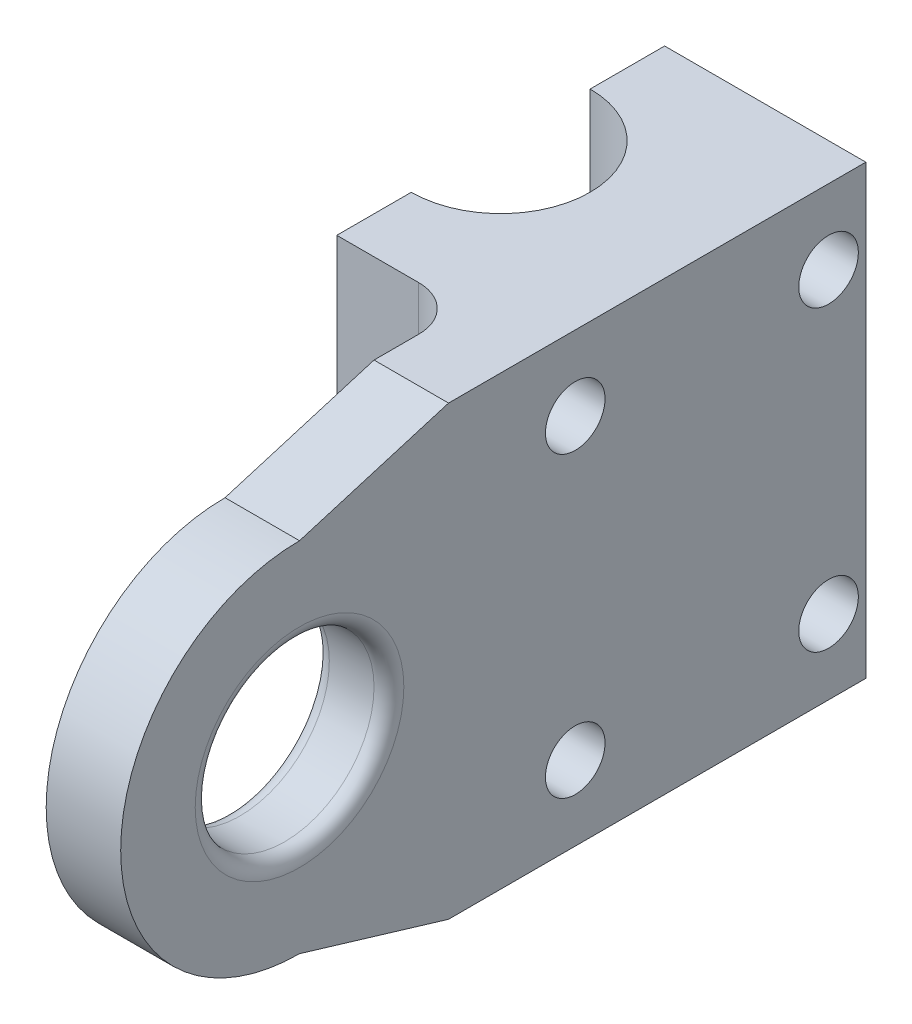
SolidWorks part; units mm, degrees
material "5052-H32"
ref_plane "Front Plane" through (0, 0, 0) normal (0, 0, 1) x (1, 0, 0)
ref_plane "Top Plane" through (0, 0, 0) normal (0, 1, 0) x (1, 0, 0)
ref_plane "Right Plane" through (0, 0, 0) normal (1, 0, 0) x (0, 0, -1)
sketch "Sketch2" plane through (0, 0, 0) normal (0, 1, 0) x (1, 0, 0)
  line L0 (0, 0) -> (0, 50) construction
  line L1 (0, 0) -> (84.2269, 0) construction
  line L2 (0, 50) -> (13.5, 50)
  line L3 (13.5, 50) -> (13.5, 0)
  line L4 (13.5, 0) -> (8.5, 0)
  line L5 (8.5, 0) -> (8.5, 25)
  line L7 (5.5, 28) -> (0, 28)
  line L8 (0, 28) -> (0, 33)
  line L9 (0, 45) -> (0, 50)
  arc A0 (0, 33) -> (0, 45) centre (0, 39) ccw
  arc A1 (8.5, 25) -> (5.5, 28) centre (5.5, 25) ccw
  dimension "D3" = 6
  dimension "D6" = 3
  dimension "D1" = 50
  dimension "D2" = 5
  dimension "D4" = 27
  dimension "D5" = 22
extrude "Boss-Extrude1" add sketch "Sketch2" along normal blind 30
sketch "Sketch3" plane through (13.5, 0, 0) normal (1, 0, 0) x (0, 0, -1)
  line L0 (0, 15) -> (50, 15) construction
  line L1 (0, 30) -> (0, 0) construction
  line L3 (12, 27) -> (22, 30)
  line L5 (0, 30) -> (50, 30) construction
  line L6 (22, 30) -> (50, 30) construction
  line L7 (50, 0) -> (22, 0) construction
  line L8 (0, 0) -> (50, 0) construction
  line L9 (22, 0) -> (12, 3)
  line L11 (50, 30) -> (50, 0) construction
  line L12 (22, 30) -> (0, 30)
  line L13 (0, 30) -> (0, 0)
  line L14 (0, 0) -> (22, 0)
  line L15 (50, 30) -> (50, 0) construction
  circle A0 centre (12, 15) radius 6
  arc A1 (12, 27) -> (12, 3) centre (12, 15) ccw
  circle A2 centre (12, 15) radius 12 construction
  circle A3 centre (30.5, 25) radius 2
  circle A4 centre (47.5, 25) radius 2
  circle A5 centre (47.5, 5) radius 2
  circle A6 centre (30.5, 5) radius 2
  dimension "D2" = 12
  dimension "D6" = 4
  dimension "D7" = 4
  dimension "D1" = 12
  dimension "D4" = 10
  dimension "D5" = 10
  dimension "D8" = 2.5
  dimension "D9" = 17
  dimension "D10" = 5
  dimension "D3" = 6
extrude "Cut-Extrude2" cut sketch "Sketch3" against normal up to next
fillet "Fillet1" radius 1 2 edges at (13.5, 15, -18) (8.5, 15, -18)
